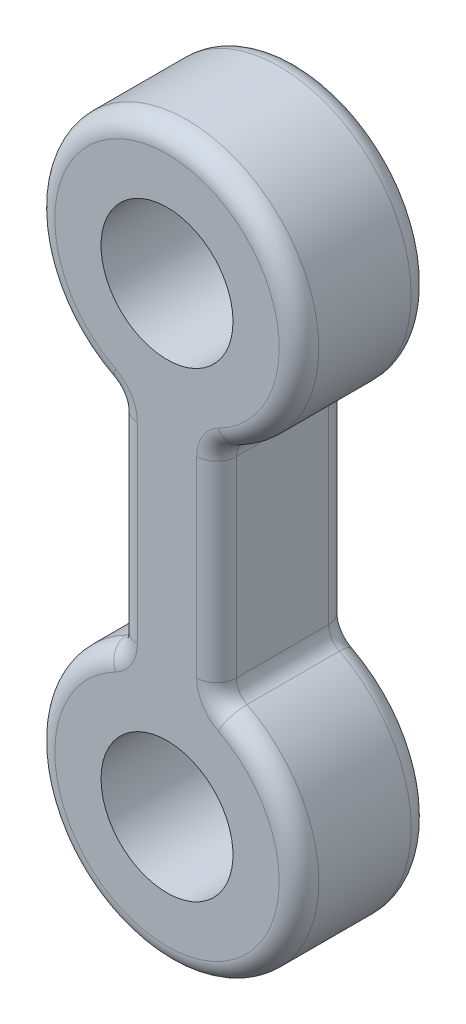
SolidWorks part; units mm, degrees
ref_plane "Front Plane" through (0, 0, 0) normal (0, 0, 1) x (1, 0, 0)
ref_plane "Top Plane" through (0, 0, 0) normal (0, 1, 0) x (1, 0, 0)
ref_plane "Right Plane" through (0, 0, 0) normal (1, 0, 0) x (0, 0, -1)
sketch "Sketch1" plane through (0, 0, 0) normal (0, 0, 1) x (1, 0, 0)
  line L0 (0, 0) -> (-28.4792, 0) construction
  line L1 (-7.5, 16.4595) -> (-7.5, -16.4595)
  line L2 (7.5, 16.4595) -> (7.5, -16.4595)
  arc A0 (7.5, 16.4595) -> (-7.5, 16.4595) centre (0, 35) ccw
  circle A1 centre (0, 35) radius 10
  circle A2 centre (0, -35) radius 10
  arc A3 (7.5, -16.4595) -> (-7.5, -16.4595) centre (0, -35) cw
  point P10 (0, 0)
  point P15 (7.5, 0)
  point P16 (-7.5, 0)
  dimension "D1" = 40
  dimension "D2" = 20
  dimension "D3" = 7.5
  dimension "D4" = 7.5
  dimension "D5" = 35
extrude "Boss-Extrude1" add sketch "Sketch1" along normal mid plane 20
fillet "Fillet1" radius 3 12 edges at (7.5, 0, 10) (7.5, 0, -10) (-7.5, 0, 10) (-7.5, 0, -10) (-7.5, -16.4595, 0) (0, -55, 10) (7.5, -16.4595, 0) (0, -55, -10) (7.5, 16.4595, 0) (0, 55, 10) (-7.5, 16.4595, 0) (0, 55, -10)
